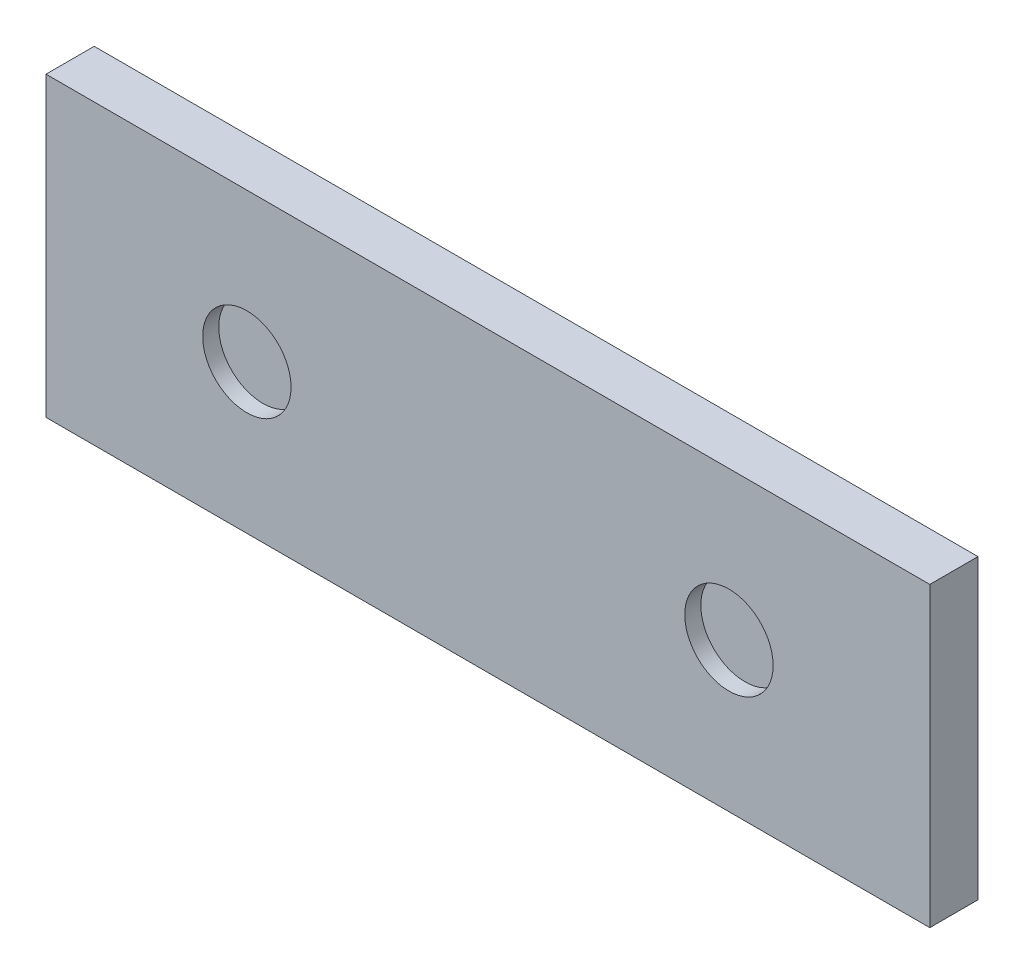
SolidWorks part; units mm, degrees
ref_plane "Front Plane" through (0, 0, 0) normal (0, 0, 1) x (1, 0, 0)
ref_plane "Top Plane" through (0, 0, 0) normal (0, 1, 0) x (1, 0, 0)
ref_plane "Right Plane" through (0, 0, 0) normal (1, 0, 0) x (0, 0, -1)
sketch "Sketch1" plane through (0, 0, 0) normal (0, 0, 1) x (1, 0, 0)
  line L1 (27.5, 9.25) -> (-27.5, 9.25)
  line L2 (27.5, 9.25) -> (27.5, -9.25)
  line L3 (27.5, -9.25) -> (-27.5, -9.25)
  line L4 (-27.5, 9.25) -> (-27.5, -9.25)
  line L5 (27.5, 9.25) -> (-27.5, -9.25) construction
  line L6 (27.5, -9.25) -> (-27.5, 9.25) construction
  point P0 (0, 0)
  dimension "D1" = 55
  dimension "D2" = 18.5
extrude "Boss-Extrude1" add sketch "Sketch1" along normal mid plane 3
sketch "Sketch2" plane through (0, 0, 1.5) normal (0, 0, 1) x (1, 0, 0)
  line L0 (15, 0) -> (-15, 0) construction
  circle A0 centre (-15, 0) radius 2.75
  circle A1 centre (15, 0) radius 2.75
  dimension "D3" = 5.5
  dimension "D1" = 15
  dimension "D2" = 30
extrude "Cut-Extrude1" cut sketch "Sketch2" against normal blind 1
